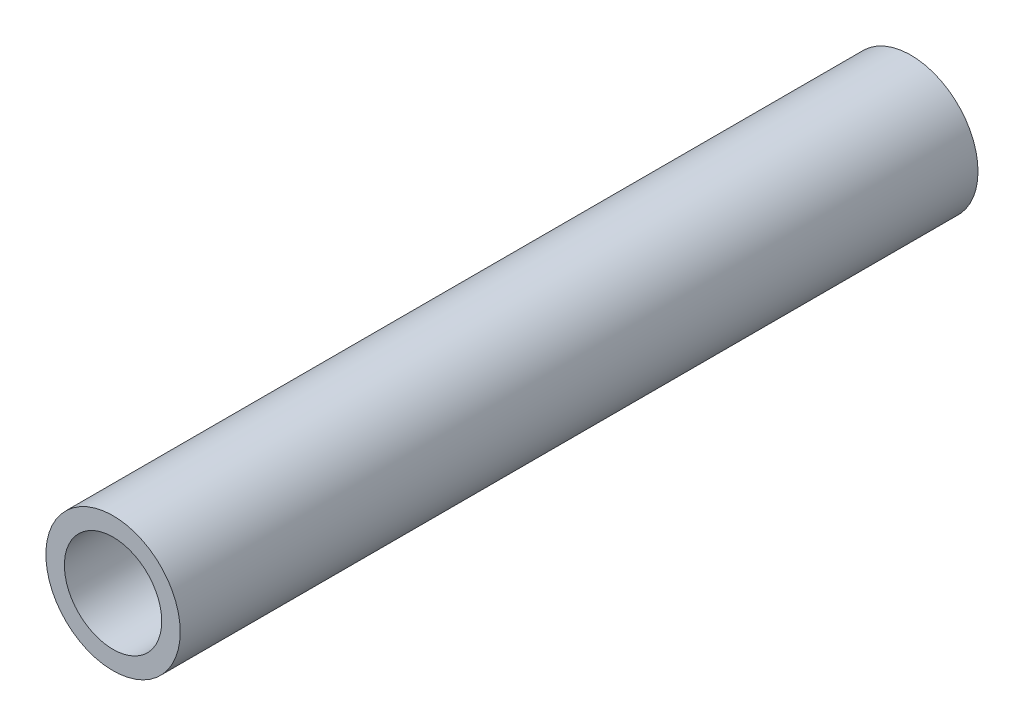
SolidWorks part; units mm, degrees
ref_plane "Front Plane" through (0, 0, 0) normal (0, 0, 1) x (1, 0, 0)
ref_plane "Top Plane" through (0, 0, 0) normal (0, 1, 0) x (1, 0, 0)
ref_plane "Right Plane" through (0, 0, 0) normal (1, 0, 0) x (0, 0, -1)
sketch "Sketch1" plane through (0, 0, 0) normal (0, 0, 1) x (1, 0, 0)
  circle A0 centre (0, 0) radius 10.6934
  circle A1 centre (0, 0) radius 7.747
  dimension "D1" = 21.3868
  dimension "D2" = 15.494
extrude "Boss-Extrude1" add sketch "Sketch1" along normal blind 127
